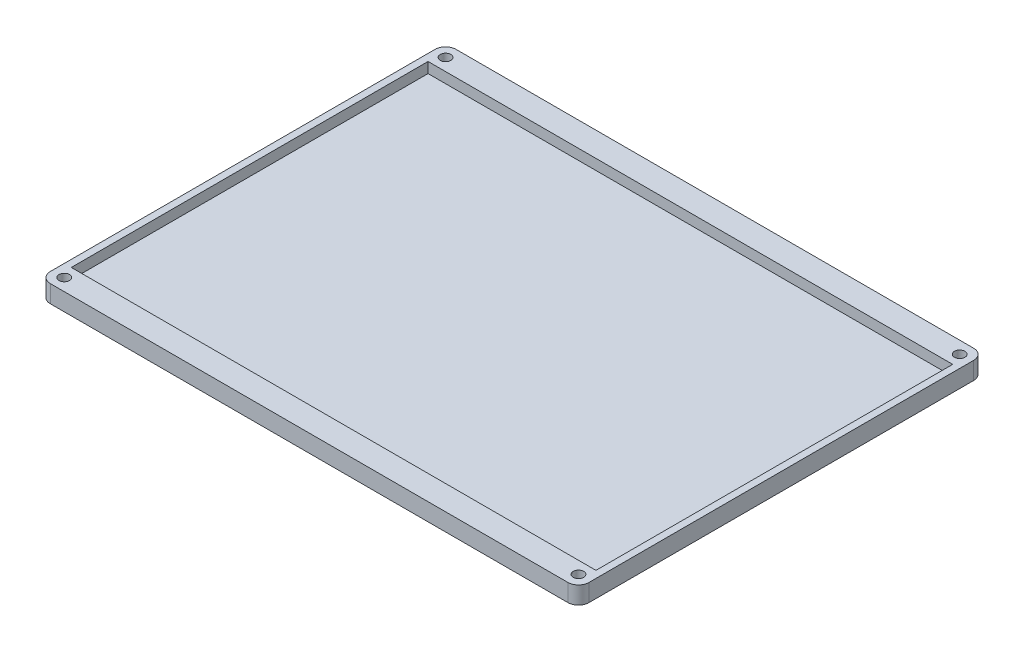
SolidWorks part; units mm, degrees
ref_plane "Front Plane" through (0, 0, 0) normal (0, 0, 1) x (1, 0, 0)
ref_plane "Top Plane" through (0, 0, 0) normal (0, 1, 0) x (1, 0, 0)
ref_plane "Right Plane" through (0, 0, 0) normal (1, 0, 0) x (0, 0, -1)
sketch "Sketch1" plane through (0, 0, 0) normal (0, 1, 0) x (1, 0, 0)
  line L1 (-77, 58) -> (77, 58)
  line L2 (-77, 58) -> (-77, -58)
  line L3 (-77, -58) -> (77, -58)
  line L4 (77, 58) -> (77, -58)
  line L5 (-77, 58) -> (77, -58) construction
  line L6 (-77, -58) -> (77, 58) construction
  point P0 (0, 0)
  dimension "D1" = 154
  dimension "D2" = 116
extrude "Boss-Extrude1" add sketch "Sketch1" along normal blind 5
sketch "Sketch2" plane through (0, 5, 0) normal (0, 1, 0) x (1, 0, 0)
  line L1 (75, -51) -> (-75, -51)
  line L2 (75, -51) -> (75, 51)
  line L3 (75, 51) -> (-75, 51)
  line L4 (-75, -51) -> (-75, 51)
  line L5 (75, -51) -> (-75, 51) construction
  line L6 (75, 51) -> (-75, -51) construction
  point P0 (0, 0)
  dimension "D1" = 150
  dimension "D2" = 102
extrude "Cut-Extrude1" cut sketch "Sketch2" against normal blind 3
sketch "Sketch3" plane through (0, 5, 0) normal (0, 1, 0) x (1, 0, 0)
  line L0 (-77, 58) -> (-77, -58) construction
  line L1 (77, 58) -> (-77, 58) construction
  line L2 (77, -58) -> (77, 58) construction
  line L3 (-77, -58) -> (77, -58) construction
  circle A0 centre (-73.5, 54.5) radius 1.5
  circle A1 centre (73.5, 54.5) radius 1.5
  circle A2 centre (73.5, -54.5) radius 1.5
  circle A3 centre (-73.5, -54.5) radius 1.5
  point P0 (-73.5, 54.5)
  point P7 (73.5, 54.5)
  point P12 (73.5, -54.5)
  point P17 (-73.5, -54.5)
  dimension "D3" = 3
  dimension "D5" = 3
  dimension "D7" = 3
  dimension "D8" = 3
  dimension "D1" = 3.5
  dimension "D2" = 3.5
  dimension "D4" = 3.5
  dimension "D6" = 3.5
extrude "Cut-Extrude2" cut sketch "Sketch3" against normal through all
fillet "Fillet1" radius 3 1 edges at (77, 2.5, 58)
fillet "Fillet2" radius 3 1 edges at (-77, 2.5, 58)
fillet "Fillet3" radius 3 1 edges at (-77, 2.5, -58)
fillet "Fillet4" radius 3 1 edges at (77, 2.5, -58)
